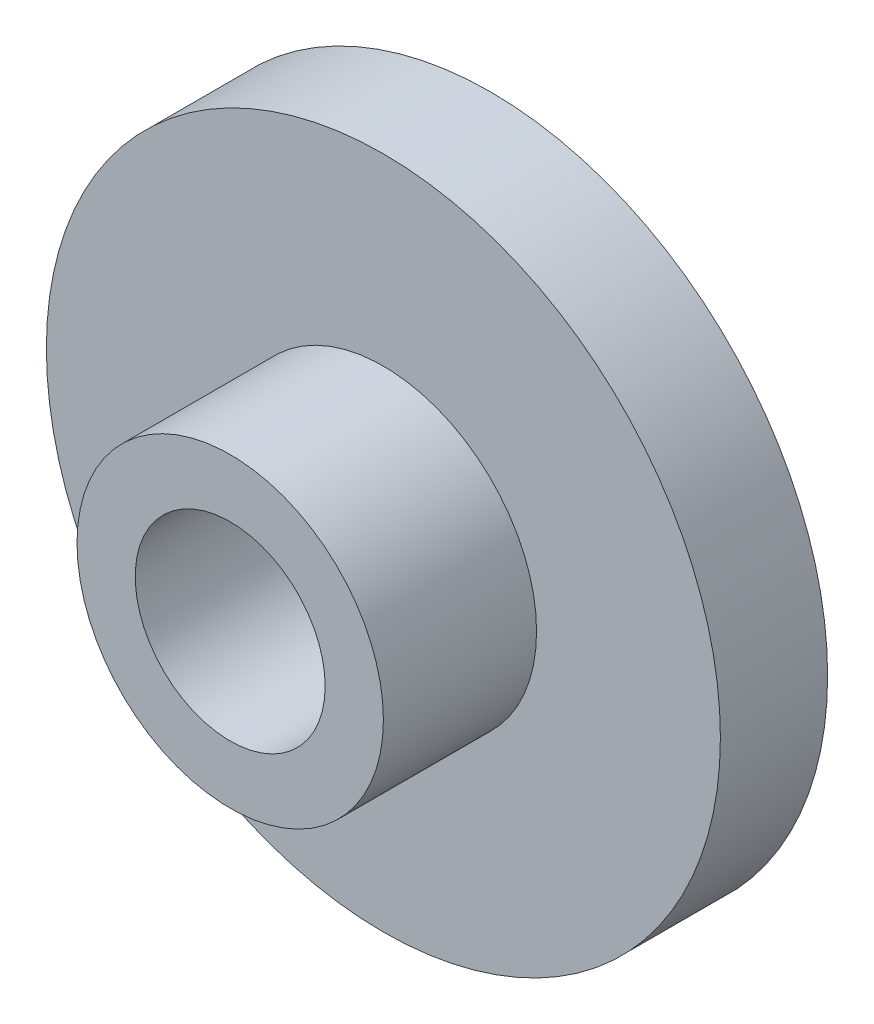
SolidWorks part; units mm, degrees
ref_plane "前视基准面" through (0, 0, 0) normal (0, 0, 1) x (1, 0, 0)
ref_plane "上视基准面" through (0, 0, 0) normal (0, 1, 0) x (1, 0, 0)
ref_plane "右视基准面" through (0, 0, 0) normal (1, 0, 0) x (0, 0, -1)
sketch "草图1" plane through (0, 0, 0) normal (0, 0, 1) x (1, 0, 0)
  circle A0 centre (0, 0) radius 11
  dimension "D1" = 22
extrude "凸台-拉伸1" add sketch "草图1" along normal blind 3.5
sketch "草图2" plane through (0, 0, 3.5) normal (0, 0, 1) x (1, 0, 0)
  circle A0 centre (0, 0) radius 5
  dimension "D1" = 10
extrude "凸台-拉伸2" add sketch "草图2" along normal blind 5
sketch "草图3" plane through (0, 0, 8.5) normal (0, 0, 1) x (1, 0, 0)
  circle A0 centre (0, 0) radius 3.1
  dimension "D1" = 6.2
extrude "切除-拉伸1" cut sketch "草图3" against normal through all
